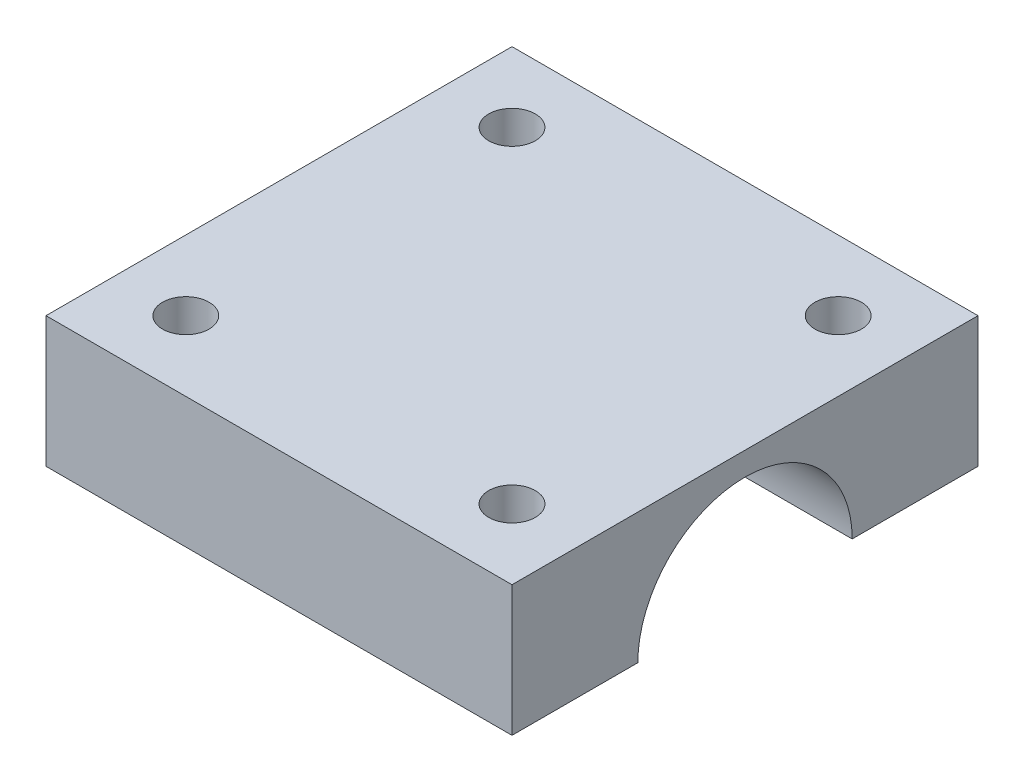
SolidWorks part; units mm, degrees
ref_plane "前视基准面" through (0, 0, 0) normal (0, 0, 1) x (1, 0, 0)
ref_plane "上视基准面" through (0, 0, 0) normal (0, 1, 0) x (1, 0, 0)
ref_plane "右视基准面" through (0, 0, 0) normal (1, 0, 0) x (0, 0, -1)
sketch "草图1" plane through (0, 0, 0) normal (0, 1, 0) x (1, 0, 0)
  line L1 (-25, -25) -> (25, -25)
  line L2 (-25, -25) -> (-25, 25)
  line L3 (-25, 25) -> (25, 25)
  line L4 (25, -25) -> (25, 25)
  line L5 (-25, -25) -> (25, 25) construction
  line L6 (-25, 25) -> (25, -25) construction
  line L7 (-17.5, -17.5) -> (17.5, -17.5) construction
  line L8 (-17.5, -17.5) -> (-17.5, 17.5) construction
  line L9 (-17.5, 17.5) -> (17.5, 17.5) construction
  line L10 (17.5, -17.5) -> (17.5, 17.5) construction
  line L11 (-17.5, -17.5) -> (17.5, 17.5) construction
  line L12 (-17.5, 17.5) -> (17.5, -17.5) construction
  circle A0 centre (-17.5, 17.5) radius 2.5
  circle A1 centre (-17.5, -17.5) radius 2.5
  circle A2 centre (17.5, 17.5) radius 2.5
  circle A3 centre (17.5, -17.5) radius 2.5
  point P1 (0, 0)
  point P6 (0, 0)
  dimension "D5" = 5
  dimension "D6" = 5
  dimension "D7" = 5
  dimension "D8" = 5
  dimension "D1" = 50
  dimension "D2" = 50
  dimension "D3" = 35
  dimension "D4" = 35
extrude "凸台-拉伸1" add sketch "草图1" along normal blind 14
sketch "草图2" plane through (-25, 0, 0) normal (-1, 0, 0) x (0, 0, 1)
  circle A0 centre (0, 0) radius 11.5
  dimension "D1" = 23
extrude "切除-拉伸1" cut sketch "草图2" against normal through all
